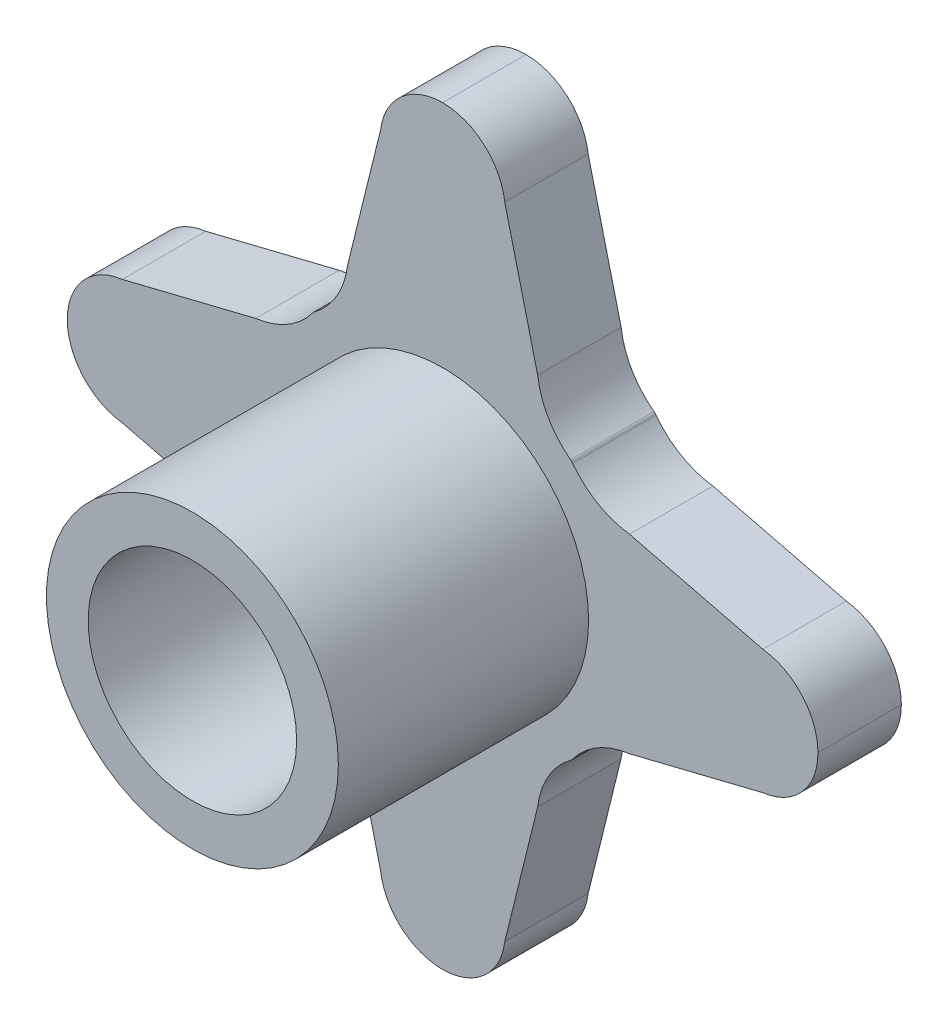
SolidWorks part; units mm, degrees
ref_plane "Front Plane" through (0, 0, 0) normal (0, 0, 1) x (1, 0, 0)
ref_plane "Top Plane" through (0, 0, 0) normal (0, 1, 0) x (1, 0, 0)
ref_plane "Right Plane" through (0, 0, 0) normal (1, 0, 0) x (0, 0, -1)
sketch "Sketch2" plane through (0, 0, 0) normal (0, 0, 1) x (1, 0, 0)
  line L0 (0, -9) -> (0, 9) construction
  line L1 (25.6195, 0) -> (-25.6195, 0) construction
  line L2 (0, 0) -> (83.1446, -83.1446) construction
  line L3 (1.49, -7.68) -> (2.28, -4.48)
  line L4 (7.68, -1.49) -> (4.48, -2.28)
  line L5 (7.68, 1.49) -> (4.48, 2.28)
  line L6 (1.49, 7.68) -> (2.28, 4.48)
  line L7 (-1.49, 7.68) -> (-2.28, 4.48)
  line L8 (-7.68, 1.49) -> (-4.48, 2.28)
  line L9 (-7.68, -1.49) -> (-4.48, -2.28)
  line L10 (-1.49, -7.68) -> (-2.28, -4.48)
  arc A0 (0, -9) -> (1.49, -7.68) centre (0.0008, -7.5) ccw
  arc A1 (2.28, -4.48) -> (3.07, -3.12) centre (4.2651, -4.7237) cw
  arc A2 (3.07, -3.12) -> (3.0984, -3.0984) centre (2.1516, -1.8876) ccw
  arc A3 (3.12, -3.07) -> (3.0984, -3.0984) centre (1.8876, -2.1516) cw
  arc A4 (4.48, -2.28) -> (3.12, -3.07) centre (4.7237, -4.2651) ccw
  arc A5 (9, 0) -> (7.68, -1.49) centre (7.5, -0.0008) cw
  arc A6 (9, 0) -> (7.68, 1.49) centre (7.5, 0.0008) ccw
  arc A7 (4.48, 2.28) -> (3.12, 3.07) centre (4.7237, 4.2651) cw
  arc A8 (3.12, 3.07) -> (3.0984, 3.0984) centre (1.8876, 2.1516) ccw
  arc A9 (3.07, 3.12) -> (3.0984, 3.0984) centre (2.1516, 1.8876) cw
  arc A10 (2.28, 4.48) -> (3.07, 3.12) centre (4.2651, 4.7237) ccw
  arc A11 (0, 9) -> (1.49, 7.68) centre (0.0008, 7.5) cw
  arc A12 (0, 9) -> (-1.49, 7.68) centre (-0.0008, 7.5) ccw
  arc A13 (-2.28, 4.48) -> (-3.07, 3.12) centre (-4.2651, 4.7237) cw
  arc A14 (-3.07, 3.12) -> (-3.0984, 3.0984) centre (-2.1516, 1.8876) ccw
  arc A15 (-3.12, 3.07) -> (-3.0984, 3.0984) centre (-1.8876, 2.1516) cw
  arc A16 (-4.48, 2.28) -> (-3.12, 3.07) centre (-4.7237, 4.2651) ccw
  arc A17 (-9, 0) -> (-7.68, 1.49) centre (-7.5, 0.0008) cw
  arc A18 (-9, 0) -> (-7.68, -1.49) centre (-7.5, -0.0008) ccw
  arc A19 (-4.48, -2.28) -> (-3.12, -3.07) centre (-4.7237, -4.2651) cw
  arc A20 (-3.12, -3.07) -> (-3.0984, -3.0984) centre (-1.8876, -2.1516) ccw
  arc A21 (-3.07, -3.12) -> (-3.0984, -3.0984) centre (-2.1516, -1.8876) cw
  arc A22 (-2.28, -4.48) -> (-3.07, -3.12) centre (-4.2651, -4.7237) ccw
  arc A23 (0, -9) -> (-1.49, -7.68) centre (-0.0008, -7.5) cw
  point P5 (0, 0)
  point P9 (0, 0)
  dimension "D7" = 1.5
  dimension "D10" = 2
  dimension "D1" = 9
  dimension "D2" = 45
  dimension "D3" = 1.49
  dimension "D4" = 0.79
  dimension "D5" = 1.32
  dimension "D6" = 3.2
  dimension "D8" = 0.79
  dimension "D9" = 1.36
extrude "Boss-Extrude1" add sketch "Sketch2" along normal blind 2
sketch "Sketch3" plane through (0, 0, 2) normal (0, 0, 1) x (1, 0, 0)
  circle A0 centre (0, 0) radius 3.5
  circle A1 centre (0, 0) radius 2.5
  dimension "D1" = 7
  dimension "D2" = 5
extrude "Boss-Extrude2" add sketch "Sketch3" along normal blind 6
sketch "Sketch4" plane through (0, 0, 0) normal (0, 0, -1) x (-1, 0, 0)
  circle A0 centre (0, 0) radius 1.25
  dimension "D1" = 2.5
extrude "Cut-Extrude1" cut sketch "Sketch4" against normal blind 1
sketch "Sketch5" plane through (0, 0, 1) normal (0, 0, -1) x (-1, 0, 0)
  circle A0 centre (0, 0) radius 0.5
  dimension "D1" = 1
extrude "Cut-Extrude2" cut sketch "Sketch5" against normal through all
